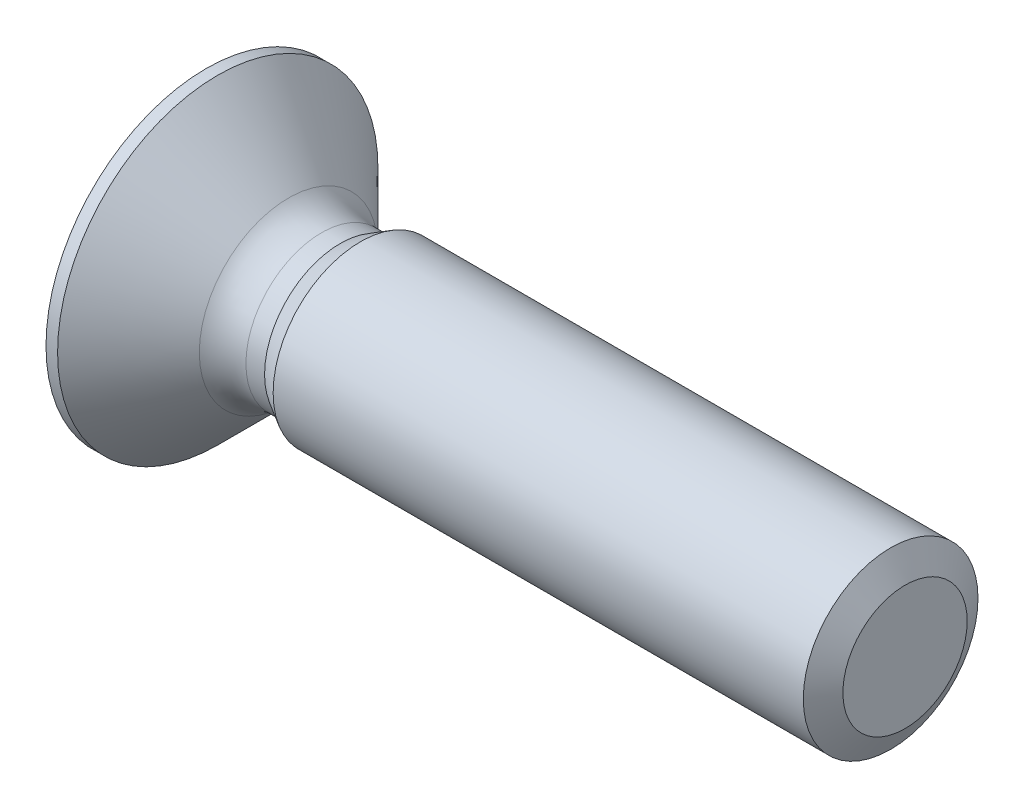
SolidWorks part; units mm, degrees
revolve "基体-旋转" add sketch "草图1" angle 360 about L0
sketch "草图1" plane through (0, 0, 0) normal (0, 0, 1) x (1, 0, 0)
  line L0 (0, 0) -> (4.4175, 0) construction
  line L1 (0, 0) -> (0, 2.75)
  line L2 (0, 2.75) -> (0.199, 2.75)
  line L3 (0.199, 2.75) -> (1.4157, 1.5333)
  line L4 (1.9814, 1.299) -> (2.3019, 1.299)
  line L5 (2.3019, 1.299) -> (2.65, 1.5)
  line L6 (2.65, 1.5) -> (12, 1.5)
  line L7 (12, 1.5) -> (12, 0)
  line L8 (0, 0) -> (12, 0)
  arc A0 (1.9814, 1.299) -> (1.4157, 1.5333) centre (1.9814, 2.099) cw
  point P12 (1.65, 1.299)
  dimension "D2" = 0.8
  dimension "D1" = 2.598
  dimension "d" = 3
  dimension "dk" = 5.5
  dimension "k" = 1.65
  dimension "D5" = 45
  dimension "a" = 1
  dimension "l" = 12
  dimension "D8" = 30
cosmetic thread "装饰螺纹线2" parameters "D1"=9.35, "D2"=2.5
material "AISI 304"
ref_plane "前视" through (0, 0, 0) normal (0, 0, 1) x (1, 0, 0)
ref_plane "上视" through (0, 0, 0) normal (0, 1, 0) x (1, 0, 0)
ref_plane "右视" through (0, 0, 0) normal (1, 0, 0) x (0, 0, -1)
sketch "尺寸草图" plane through (0, 0, 0) normal (0, 0, 1) x (1, 0, 0)
  line L0 (0, 0) -> (12, 0)
  point P3 (1.65, 0)
  point P4 (1, 0)
  point P5 (3, 0)
  point P6 (5.5, 0)
  point P7 (8.8, 0)
  point P8 (3.5943, 0)
  point P9 (11.2, 0)
  point P10 (9.9, 0)
  point P11 (11.5, 0)
  dimension "d" = 3
  dimension "dk" = 5.5
  dimension "k" = 1.65
  dimension "a" = 1
  dimension "l" = 12
  dimension "r" = 0.8
  dimension "m" = 3.2
  dimension "h" = 2.1
  dimension "p" = 0.5
sketch "草图2" plane through (0, 0, 0) normal (0, 0, 1) x (1, 0, 0)
  line L0 (11.7527, 1.5) -> (12.2527, 1.5)
  line L1 (12.2527, 1.5) -> (12, 1.067)
  line L2 (12, 1.067) -> (11.7527, 1.5)
  line L3 (12, -1.5) -> (12, 1.5) construction
  line L6 (0, 0) -> (-0.4315, 0) construction
  dimension "D1" = 0.5
  dimension "D2" = 0.433
  dimension "D3" = 1.5
  dimension "D4" = 60
revolve "切除-旋转1" cut sketch "草图2" angle 360 about L6
pattern_linear "阵列(线性)1" [suppressed] count 19 spacing 0.5 along (1, 0, 0)
sketch "草图3" plane through (0, 0, 0) normal (-1, 0, 0) x (0, 0, 1)
  line L0 (0, 0) -> (1.6329, 0) construction
  line L1 (0, 0) -> (0, 0.8499) construction
  line L2 (-1.6, 0.25) -> (1.6, 0.25)
  line L3 (-1.6, 0.25) -> (-1.6, -0.25)
  line L4 (-1.6, -0.25) -> (1.6, -0.25)
  line L5 (1.6, 0.25) -> (1.6, -0.25)
  dimension "m" = 3.2
  dimension "D1" = 0.5
ref_plane "基准面1" through (2.1, 0, 0) normal (-1, 0, 0) x (0, 0, 1)
sketch "草图4" plane through (2.1, 0, 0) normal (-1, 0, 0) x (0, 0, 1)
  point P0 (0, 0)
loft "切除-放样1" cut profiles "草图3", "草图4"
pattern_circular "阵列(圆周)1" count 2 every 90 about axis through (0, 0, 0) along (1, 0, 0) of "切除-放样1"
equation "\"l@草图1\" = \"l@尺寸草图\""
equation "\"k@草图1\" = \"k@尺寸草图\""
equation "\"a@草图1\" = \"a@尺寸草图\""
equation "\"d@草图1\" = \"d@尺寸草图\""
equation "\"dk@草图1\" = \"dk@尺寸草图\""
equation "\"D2@草图1\" = \"r@尺寸草图\""
equation "\"m@草图3\" = \"m@尺寸草图\""
equation "\"h@基准面1\" = \"h@尺寸草图\""
equation "\"D3@阵列(线性)1\" = \"p@尺寸草图\""
equation "\"D3@草图2\" = \"d@草图1\" / 2"
equation "\"D1@装饰螺纹线2\" = \"l@草图1\" - \"k@草图1\" - \"a@草图1\""
equation "\"D2@装饰螺纹线2\" = \"d@尺寸草图\"- \"p@尺寸草图\""
equation "\"D1@阵列(线性)1\" = (  \"l@草图1\" - \"k@草图1\" - \"a@草图1\" )  / \"p@尺寸草图\""
equation "\"D1@草图3\" = \"p@尺寸草图\""
equation "\"D1@草图1\" = \"d@尺寸草图\"*0.866"
equation "\"D2@草图2\" = \"p@尺寸草图\"*0.866"
equation "\"D1@草图2\" = \"p@尺寸草图\""
